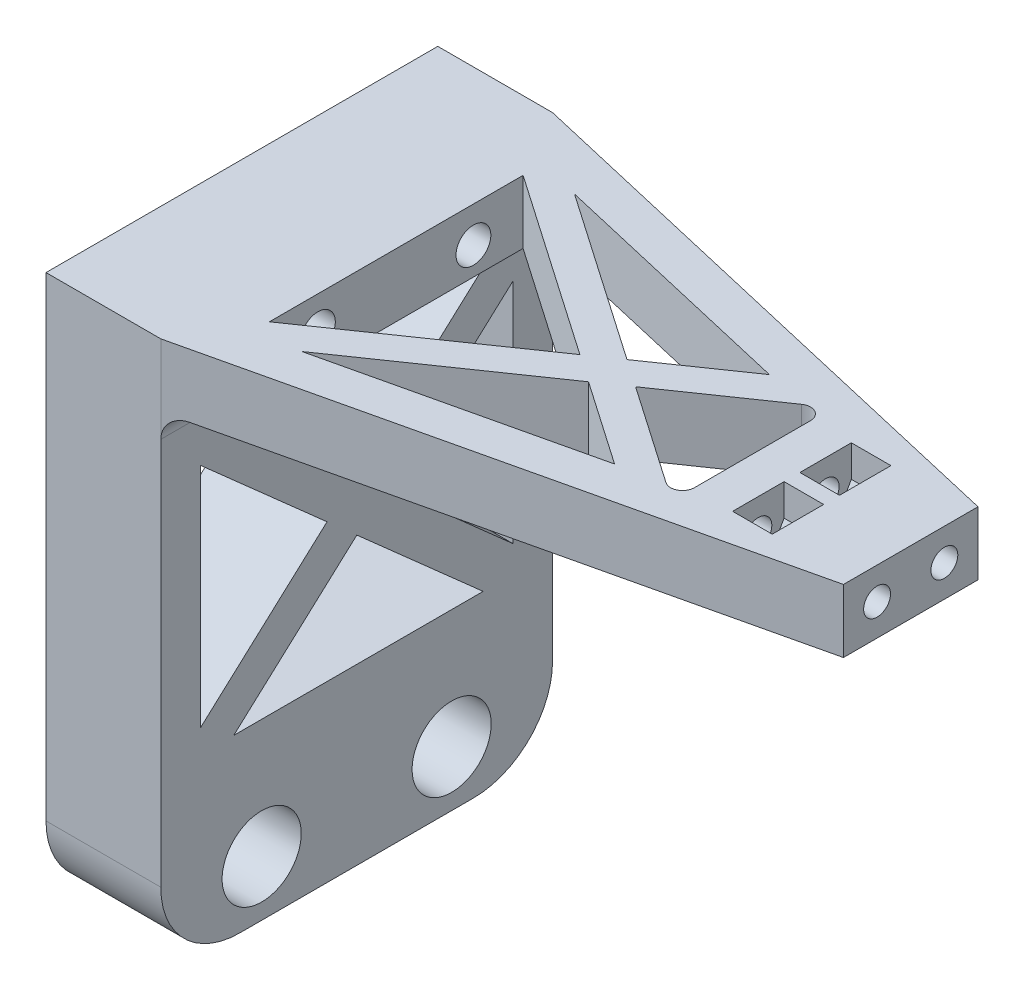
SolidWorks part; units mm, degrees
ref_plane "Front Plane" through (0, 0, 0) normal (0, 0, 1) x (1, 0, 0)
ref_plane "Top Plane" through (0, 0, 0) normal (0, 1, 0) x (1, 0, 0)
ref_plane "Right Plane" through (0, 0, 0) normal (1, 0, 0) x (0, 0, -1)
sketch "Sketch1" plane through (0, 0, 0) normal (0, 1, 0) x (1, 0, 0)
  line L1 (-7.25, -24.75) -> (7.25, -24.75)
  line L2 (-7.25, -24.75) -> (-7.25, 24.75)
  line L3 (-7.25, 24.75) -> (7.25, 24.75)
  line L4 (7.25, -24.75) -> (7.25, 24.75)
  line L5 (-7.25, -24.75) -> (7.25, 24.75) construction
  line L6 (-7.25, 24.75) -> (7.25, -24.75) construction
  point P0 (0, 0)
  dimension "D1" = 49.5
  dimension "D2" = 14.5
extrude "Boss-Extrude1" add sketch "Sketch1" along normal blind 70
fillet "Fillet1" radius 10 2 edges at (0, 0, -24.75) (0, 0, 24.75)
sketch "Sketch2" plane through (7.25, 0, 0) normal (1, 0, 0) x (0, 0, -1)
  line L0 (0, 0) -> (-12, 0) construction
  line L1 (-14.75, 0) -> (14.75, 0) construction
  line L2 (-12, 0) -> (-12, 2) construction
  line L3 (-12, 2) -> (-12, 7) construction
  line L4 (0, 0) -> (0, 10.6339) construction
  line L5 (12, 2) -> (12, 7) construction
  line L6 (12, 0) -> (12, 2) construction
  circle A0 centre (-12, 7) radius 5
  circle A1 centre (12, 7) radius 5
  dimension "D1" = 12
  dimension "D2" = 2
  dimension "D3" = 5
extrude "Cut-Extrude1" cut sketch "Sketch2" against normal through all
sketch "Sketch3" plane through (0, 70, 0) normal (0, 1, 0) x (1, 0, 0)
  line L0 (77.25, 8.5) -> (77.25, -8.5)
  line L1 (7.25, 0) -> (77.25, 0) construction
  line L2 (7.25, -24.75) -> (7.25, 24.75) construction
  line L3 (7.25, 24.75) -> (7.25, -24.75)
  line L4 (7.25, -24.75) -> (77.25, -8.5)
  line L5 (7.25, 24.75) -> (77.25, 8.5)
  point P7 (77.25, 0)
  dimension "D1" = 17
  dimension "D2" = 70
extrude "Boss-Extrude2" add sketch "Sketch3" against normal blind 8
sketch "Sketch5" plane through (77.25, 0, 0) normal (1, 0, 0) x (0, 0, -1)
  line L0 (-8.5, 66) -> (0, 66) construction
  line L1 (-8.5, 62) -> (-8.5, 70) construction
  line L2 (0, 66) -> (8.5, 66) construction
  line L3 (8.5, 62) -> (8.5, 70) construction
  circle A0 centre (-4.25, 66) radius 1.7
  circle A1 centre (4.25, 66) radius 1.7
  dimension "D2" = 3.4
  dimension "D3" = 3.4
  dimension "D1" = 8.5
extrude "Cut-Extrude2" cut sketch "Sketch5" against normal blind 15
ref_plane "Plane1" through (62.25, 0, 0) normal (1, 0, 0) x (0, 0, -1)
sketch "Sketch7" plane through (62.25, 0, 0) normal (1, 0, 0) x (0, 0, -1)
  line L0 (-7.5, 66) -> (-7.5, 70)
  line L1 (-1, 66) -> (-2.625, 68.8146) construction
  line L2 (-2.625, 68.8146) -> (-5.875, 68.8146) construction
  line L3 (-5.875, 68.8146) -> (-7.5, 66) construction
  line L4 (-7.5, 66) -> (-5.875, 63.1854)
  line L5 (-5.875, 63.1854) -> (-2.625, 63.1854)
  line L6 (-2.625, 63.1854) -> (-1, 66)
  line L7 (7.5, 66) -> (5.875, 68.8146) construction
  line L8 (5.875, 68.8146) -> (2.625, 68.8146) construction
  line L9 (2.625, 68.8146) -> (1, 66) construction
  line L10 (1, 66) -> (2.625, 63.1854)
  line L11 (2.625, 63.1854) -> (5.875, 63.1854)
  line L12 (5.875, 63.1854) -> (7.5, 66)
  line L13 (-8.5, 70) -> (8.5, 70) construction
  line L14 (-7.5, 70) -> (-1, 70)
  line L15 (-1, 70) -> (-1, 66)
  line L16 (1, 66) -> (1, 70)
  line L17 (1, 70) -> (7.5, 70)
  line L18 (7.5, 70) -> (7.5, 66)
  circle A0 centre (-4.25, 66) radius 2.8146 construction
  circle A1 centre (4.25, 66) radius 2.8146 construction
  dimension "D1" = 6.5
  dimension "D2" = 6.5
extrude "Cut-Extrude3" cut sketch "Sketch7" along normal blind 5
sketch "Sketch8" plane through (7.25, 0, 0) normal (1, 0, 0) x (0, 0, -1)
  line L0 (-24.75, 62) -> (-24.75, 17) construction
  line L1 (-24.75, 62) -> (-24.75, 10) construction
  line L2 (-24.75, 17) -> (24.75, 17) construction
  line L3 (24.75, 62) -> (24.75, 10) construction
  line L4 (0.0214, 36.1408) -> (15.9803, 22)
  line L5 (-8.5, 62) -> (8.5, 62) construction
  line L7 (-19.75, 24.9241) -> (-19.75, 53.6598)
  line L8 (-15.9803, 57) -> (15.5335, 57)
  line L9 (19.75, 25.3402) -> (19.75, 54.0759)
  line L10 (-0.0214, 42.8592) -> (15.5335, 57)
  line L11 (3.7428, 39.5239) -> (19.75, 25.3402)
  line L12 (-19.75, 53.6598) -> (-3.7428, 39.4761)
  line L13 (-19.75, 24.9241) -> (-3.7428, 39.4761)
  line L14 (-15.9803, 57) -> (-0.0214, 42.8592)
  line L15 (-15.5335, 22) -> (15.9803, 22)
  line L16 (-15.5335, 22) -> (0.0214, 36.1408)
  line L17 (3.7428, 39.5239) -> (19.75, 54.0759)
  point P5 (0, 39.5)
  dimension "D1" = 45
  dimension "D2" = 5
  dimension "D3" = 5
extrude "Cut-Extrude4" cut sketch "Sketch8" against normal through all
sketch "Sketch9" plane through (0, 70, 0) normal (0, 1, 0) x (1, 0, 0)
  line L0 (57.25, 13.1429) -> (57.25, -13.1429) construction
  line L1 (62.25, 7.5) -> (62.25, 1) construction
  line L2 (7.25, 24.75) -> (7.25, -24.75) construction
  line L3 (49.616, 9.7821) -> (17.551, 17.2257)
  line L4 (12.25, 16.0257) -> (12.25, -16.0257)
  line L5 (17.551, -17.2257) -> (49.616, -9.7821)
  line L6 (-7.25, -24.75) -> (7.25, -24.75)
  line L7 (7.25, -24.75) -> (77.25, -8.5)
  line L8 (77.25, -8.5) -> (77.25, 8.5)
  line L9 (77.25, 8.5) -> (7.25, 24.75)
  line L10 (7.25, 24.75) -> (-7.25, 24.75)
  line L11 (-7.25, 24.75) -> (-7.25, -24.75)
  line L13 (7.25, -24.75) -> (57.25, -13.1429) construction
  line L15 (57.25, 13.1429) -> (7.25, 24.75) construction
  line L18 (57.25, 10.1933) -> (57.25, -10.1933)
  line L21 (12.25, 16.0257) -> (35.453, 0)
  line L22 (49.616, 9.7821) -> (38.9722, 2.4307)
  line L23 (17.551, 17.2257) -> (38.9722, 2.4307)
  line L24 (57.25, 10.1933) -> (42.4915, 0)
  line L27 (42.4915, 0) -> (57.25, -10.1933)
  line L28 (38.9722, -2.4307) -> (49.616, -9.7821)
  line L29 (35.453, 0) -> (12.25, -16.0257)
  line L30 (38.9722, -2.4307) -> (17.551, -17.2257)
  dimension "D2" = 5
  dimension "D4" = 69.264
  dimension "D1" = 0
extrude "Cut-Extrude5" cut sketch "Sketch9" against normal blind 10 contours L29 L21 L4 | L3 L23 L22 | L24 L27 L18 | L28 L30 L5
fillet "Fillet2" radius 1.5 2 edges at (57.25, 66, 10.1933) (57.25, 66, -10.1933)
fillet "Fillet3" radius 3 1 edges at (7.25, 62, 0)
sketch "Sketch10" plane through (-7.25, 0, 0) normal (-1, 0, 0) x (0, 0, 1)
  line L0 (-24.75, 65.5) -> (-9.75, 65.5) construction
  line L1 (-24.75, 70) -> (-24.75, 10) construction
  line L2 (-9.75, 65.5) -> (-9.75, 70) construction
  line L3 (-24.75, 70) -> (24.75, 70) construction
  line L4 (0, 70) -> (0.2234, 57) construction
  line L5 (-15.5335, 57) -> (15.9803, 57) construction
  circle A0 centre (-9.75, 65.5) radius 2.2
  circle A1 centre (9.8989, 65.8377) radius 2.2
  dimension "D3" = 4.4
  dimension "D1" = 4.5
  dimension "D2" = 15
extrude "Cut-Extrude6" cut sketch "Sketch10" against normal up to surface (19.5 mm away) up to face at (12.25, 66, 0)
sketch "Sketch11" plane through (62.25, 0, 0) normal (1, 0, 0) x (0, 0, -1)
  circle A0 centre (4.25, 66) radius 1.7 construction
  circle A1 centre (-4.25, 66) radius 1.7 construction
  circle A2 centre (4.25, 66) radius 1.7
  circle A3 centre (-4.25, 66) radius 1.7
extrude "Cut-Extrude7" cut sketch "Sketch11" against normal blind 3
